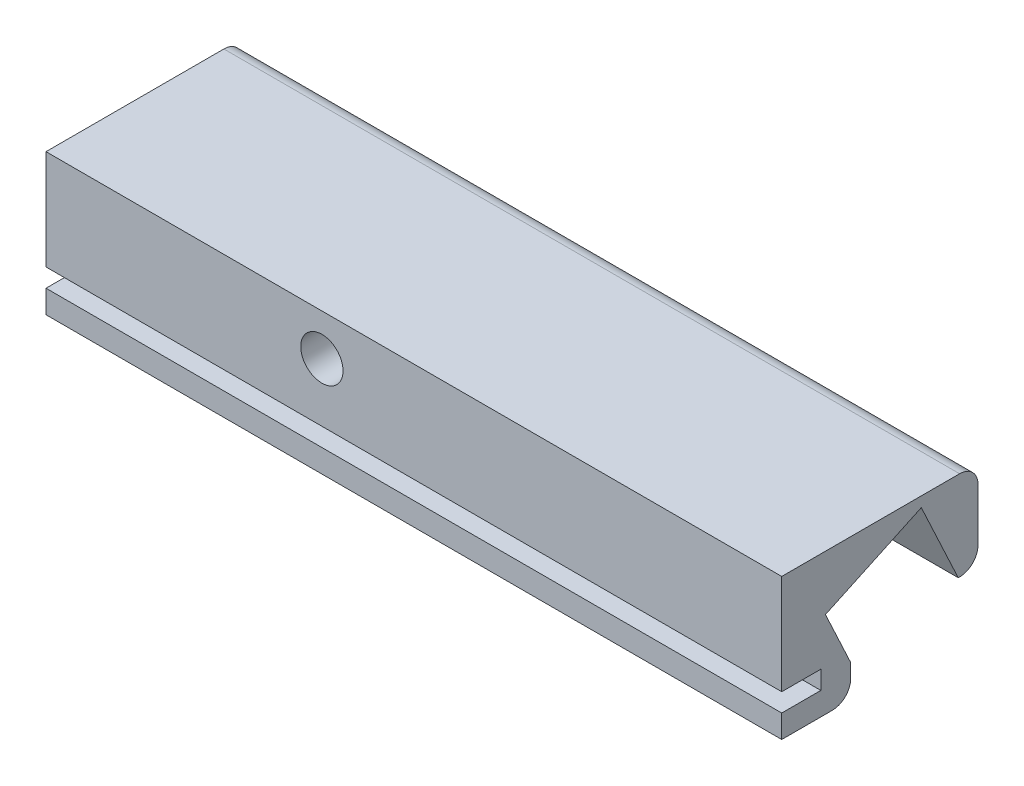
SolidWorks part; units mm, degrees
ref_plane "Front Plane" through (0, 0, 0) normal (0, 0, 1) x (1, 0, 0)
ref_plane "Top Plane" through (0, 0, 0) normal (0, 1, 0) x (1, 0, 0)
ref_plane "Right Plane" through (0, 0, 0) normal (1, 0, 0) x (0, 0, -1)
sketch "Sketch1" plane through (0, 0, 0) normal (1, 0, 0) x (0, 0, -1)
  line L0 (0, 0) -> (5.4995, 0)
  line L2 (21.3407, 7.6355) -> (21.3407, 13.3601)
  line L3 (19.3407, 15.3601) -> (0, 15.3601)
  line L4 (0, 15.3601) -> (0, 0)
  line L6 (19.1904, 5.6412) -> (17.9225, 8.3601)
  line L7 (17.9225, 8.3601) -> (7.5, 3.5)
  line L8 (7.5, 3.5) -> (7.5, 2.0005)
  arc A0 (19.3407, 15.3601) -> (21.3407, 13.3601) centre (19.3407, 13.3601) cw
  arc A1 (19.1904, 5.6412) -> (21.3407, 7.6355) centre (19.3407, 7.6355) ccw
  arc A2 (5.4995, 0) -> (7.5, 2.0005) centre (5.4995, 2.0005) ccw
  dimension "D7" = 4
  dimension "D4" = 4
  dimension "D8" = 4.0011
  dimension "D3" = 11.5
  dimension "D1" = 7.5
  dimension "D5" = 7
  dimension "D6" = 3
extrude "ProfileBoss-Extrude1" add sketch "Sketch1" along normal blind 80
sketch "Sketch2" plane through (0, 0.0022, 0.001) normal (0, -0.9063, -0.4226) x (1, 0, 0)
  line L0 (80, -8.2765) -> (80, -19.7765) construction
  line L1 (0, -8.2765) -> (0, -19.7765) construction
  line L2 (80, -8.2765) -> (0, -8.2765) construction
  circle A0 centre (43.85, -14.0265) radius 2.3
  dimension "D1" = 4.6
  dimension "D2" = 5.75
  dimension "D3" = 36.15
  dimension "D4" = 43.85
extrude "LedStripMountHolesCut-Extrude1" cut sketch "Sketch2" against normal blind 4.5
sketch "Sketch4" plane through (0, 0.0022, 0.001) normal (0, -0.9063, -0.4226) x (1, 0, 0)
  line L0 (80, -8.2765) -> (80, -19.7765) construction
  line L5 (80, -19.7765) -> (0, -19.7765) construction
  line L6 (52, -8.2765) -> (80, -8.2765)
  line L7 (52, -8.2765) -> (52, -19.7765)
  line L8 (52, -19.7765) -> (80, -19.7765)
  line L9 (80, -8.2765) -> (80, -19.7765)
  line L10 (80, -8.2765) -> (0, -8.2765) construction
  dimension "D2" = 28
extrude "PowerConnectorCut-Extrude4" cut sketch "Sketch4" against normal blind 6.5
sketch "Sketch3" plane through (0, 0, 0) normal (0, 0, 1) x (1, 0, 0)
  line L1 (80, 15.3601) -> (80, 0) construction
  circle A0 centre (30, 10.8601) radius 2.3
  dimension "D1" = 4.6
  dimension "D4" = 4.5
  dimension "D2" = 50
extrude "MountingHolesCut-Extrude3" cut sketch "Sketch3" against normal blind 4.5
sketch "Sketch5" plane through (0, 0, 0) normal (0, 0, 1) x (1, 0, 0)
  line L0 (80, 15.3601) -> (80, 0) construction
  line L1 (0, 4.5) -> (80, 4.5)
  line L2 (0, 4.5) -> (0, 2.5)
  line L3 (0, 2.5) -> (80, 2.5)
  line L4 (80, 4.5) -> (80, 2.5)
  line L5 (0, 15.3601) -> (0, 0) construction
  line L6 (80, 0) -> (0, 0) construction
  dimension "D1" = 2.5
  dimension "D2" = 2
extrude "XAxisCableCut-Extrude1" cut sketch "Sketch5" against normal blind 4.25
equation "\"LightStripShortLength\"= 80mm"
equation "\"D1@ProfileBoss-Extrude1\"=\"LightStripShortLength\""
equation "\"LightStripWidth\"= 11.5mm'Spec"
equation "\"D3@Sketch1\"=\"LightStripWidth\""
equation "\"D2@Sketch2\"=\"LightStripWidth\"/2"
equation "\"LightStripMountHoleFromLeftOrRightEdge\"= ( \"LightStipLength\" - \"LightStripDistanceBetweenMountingHoles\" ) / 2"
equation "\"LightStripGuideMountingHoleFromLeftOrRightSide\"= 50mm"
equation "\"D3@Sketch2\"=\"LightStripMountHoleFromLeftOrRightEdge\""
equation "\"D2@Sketch3\"=\"LightStripGuideMountingHoleFromLeftOrRightSide\""
equation "\"LightStripGuideMountingHoleFromTop\"=4.5"
equation "\"D4@Sketch3\"=\"LightStripGuideMountingHoleFromTop\""
equation "\"LightStipLength\"= 270mm'From Step file"
equation "\"LightStripDistanceBetweenMountingHoles\"= 197.7mm'From Step file"
